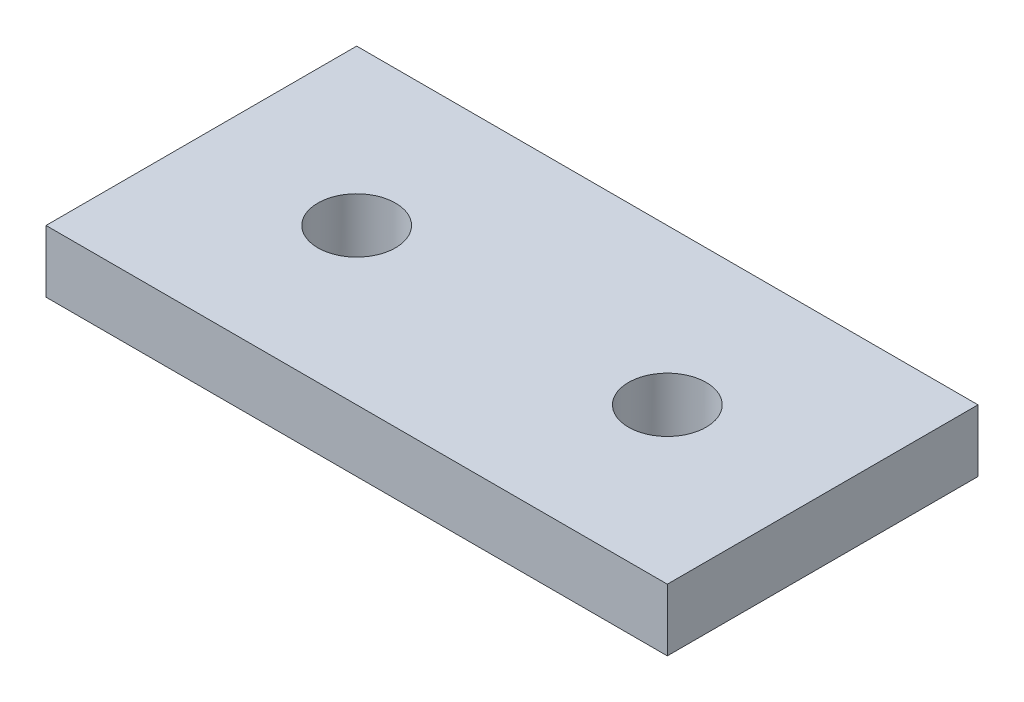
SolidWorks part; units mm, degrees
ref_plane "Front Plane" through (0, 0, 0) normal (0, 0, 1) x (1, 0, 0)
ref_plane "Top Plane" through (0, 0, 0) normal (0, 1, 0) x (1, 0, 0)
ref_plane "Right Plane" through (0, 0, 0) normal (1, 0, 0) x (0, 0, -1)
sketch "Sketch1" plane through (0, 0, 0) normal (0, 1, 0) x (1, 0, 0)
  line L0 (0, 0) -> (0, 76.2)
  line L1 (0, 76.2) -> (25.4, 76.2)
  line L2 (25.4, 76.2) -> (25.4, 25.4)
  line L3 (25.4, 25.4) -> (76.2, 25.4)
  line L4 (76.2, 25.4) -> (76.2, 0)
  line L5 (76.2, 0) -> (0, 0)
  dimension "D1" = 76.2
  dimension "D2" = 76.2
  dimension "D3" = 25.4
  dimension "D4" = 25.4
extrude "Boss-Extrude1" add sketch "Sketch1" along normal blind 5.08
sketch "Sketch2" plane through (0, 5.08, 0) normal (0, 1, 0) x (1, 0, 0)
  line L0 (12.7, 63.5) -> (12.7, 12.7)
  line L1 (12.7, 12.7) -> (63.5, 12.7)
  line L2 (25.4, 76.2) -> (0, 76.2) construction
  line L3 (0, 0) -> (76.2, 0) construction
  line L4 (0, 76.2) -> (0, 0) construction
  line L5 (76.2, 0) -> (76.2, 25.4) construction
  point P11 (38.1, 12.7)
  point P12 (12.7, 63.5)
  point P13 (12.7, 12.7)
  point P14 (63.5, 12.7)
  point P15 (12.7, 38.1)
  dimension "D1" = 12.7
  dimension "D2" = 12.7
  dimension "D3" = 12.7
  dimension "D4" = 12.7
hole_wizard "1/4 (0.25) Diameter Hole1" positions "Sketch3" profile "Sketch4" hole size "1/4" standard "ANSI Inch"
sketch "Sketch3" plane through (0, 5.08, 0) normal (0, 1, 0) x (1, 0, 0)
  point P0 (12.7, 63.5)
  point P3 (12.7, 38.1)
  point P6 (12.7, 12.7)
  point P9 (38.1, 12.7)
  point P12 (63.5, 12.7)
sketch "Sketch4" plane through (12.7, 5.08, -63.5) normal (1, 0, 0) x (0, 0, 1)
  line L0 (0, 0) -> (0, 27.3077)
  line L1 (0, 27.3077) -> (3.175, 25.4)
  line L2 (3.175, 25.4) -> (3.175, 0)
  line L5 (3.175, 0) -> (0, 0)
  line L10 (0, 27.3077) -> (-3.175, 25.4) construction
  line L11 (0, -6.35) -> (0, 107.95) construction
  dimension "Hole Dia." = 6.35
  dimension "Hole Depth" = 25.4
  dimension "Drill Angle" = 118
sketch "Sketch5" plane through (0, 0, -76.2) normal (0, 0, -1) x (-1, 0, 0)
  line L4 (-25.4, 0) -> (0, 0)
  line L5 (0, 0) -> (0, 5.08)
  line L6 (0, 5.08) -> (-25.4, 5.08)
  line L7 (-25.4, 5.08) -> (-25.4, 0)
  line L8 (-25.4, 0) -> (0, 0)
  line L9 (0, 0) -> (0, 5.08)
  line L10 (0, 5.08) -> (-25.4, 5.08)
  line L11 (-25.4, 5.08) -> (-25.4, 0)
  dimension "D1" = 0
extrude "Cut-Extrude1" cut sketch "Sketch5" against normal through all both and the other way through all
